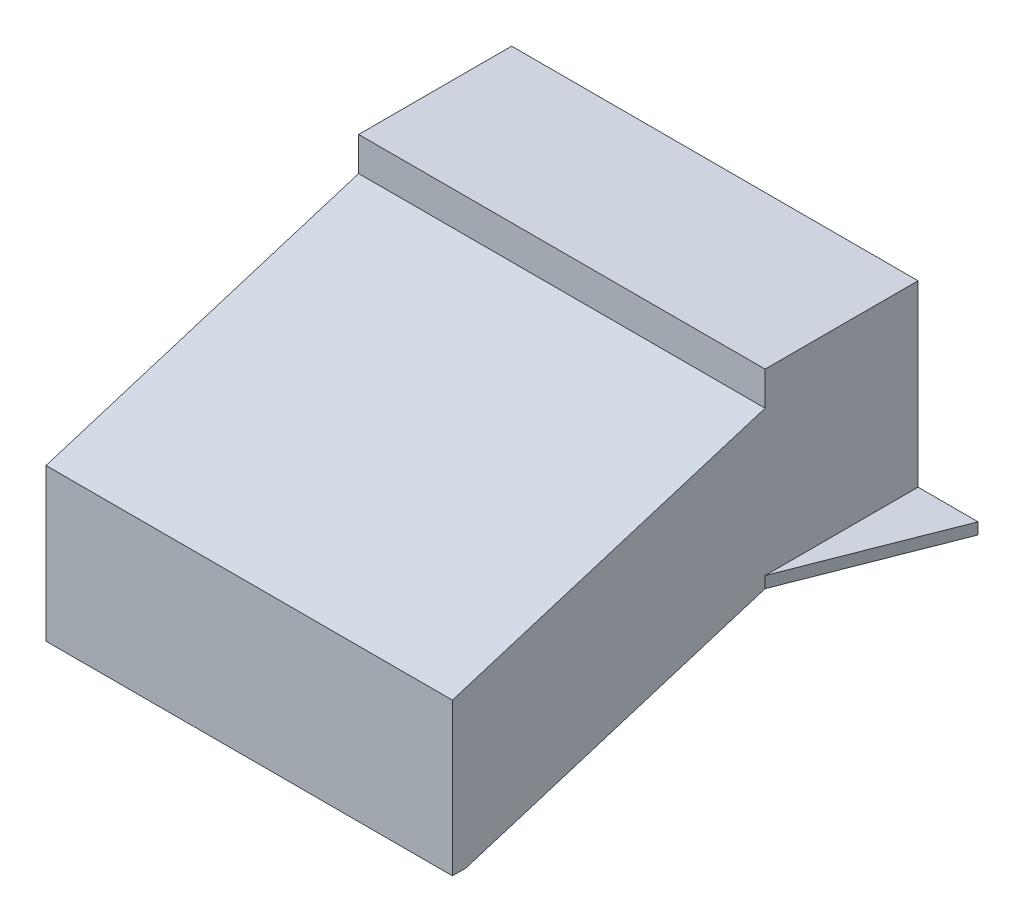
SolidWorks part; units mm, degrees
ref_plane "Front Plane" through (0, 0, 0) normal (0, 0, 1) x (1, 0, 0)
ref_plane "Top Plane" through (0, 0, 0) normal (0, 1, 0) x (1, 0, 0)
ref_plane "Right Plane" through (0, 0, 0) normal (1, 0, 0) x (0, 0, -1)
sketch "Sketch2" plane through (0, 0, 0) normal (0, 1, 0) x (1, 0, 0)
  line L1 (0, 0) -> (91, 0)
  line L2 (0, 0) -> (0, 67)
  line L3 (0, 67) -> (91, 67)
  line L4 (91, 0) -> (91, 67)
  dimension "D1" = 91
  dimension "D2" = 67
extrude "Boss-Extrude10" add sketch "Sketch2" along normal blind 55.68
sketch "Sketch24" plane through (0, 0, 0) normal (-1, 0, 0) x (0, 0, 1)
  line L0 (-67, 0) -> (-67, 20.68)
  line L1 (-67, 55.68) -> (-67, 0) construction
  line L2 (-67, 20.68) -> (0, 0)
  line L3 (0, 0) -> (-67, 0)
extrude "Cut-Extrude13" cut sketch "Sketch24" against normal blind 99
sketch "Sketch26" plane through (0, 0, 0) normal (-1, 0, 0) x (0, 0, 1)
  line L0 (0, 55.68) -> (0, 35)
  line L1 (0, 55.68) -> (0, 0) construction
  line L2 (-67, 55.68) -> (0, 55.68)
  line L3 (0, 35) -> (-67, 55.68)
extrude "Cut-Extrude14" cut sketch "Sketch26" against normal blind 99
sketch "Sketch28" plane through (0, 0, 0) normal (0, -0.9555, -0.2949) x (-1, 0, 0)
  line L0 (0, 0) -> (-2, 0) construction
  line L1 (0, 0) -> (-91, 0) construction
  line L2 (-91, 0) -> (-89, 0) construction
  line L4 (-89, 0) -> (-2, 0)
  line L5 (-89, 0) -> (-89, 97.6529)
  line L6 (-89, 97.6529) -> (-2, 97.6529)
  line L7 (-2, 0) -> (-2, 97.6529)
extrude "Cut-Extrude16" cut sketch "Sketch28" against normal blind 31
sketch "Sketch29" plane through (0, 0, -67) normal (0, 0, -1) x (-1, 0, 0)
  line L1 (-91, 55.68) -> (0, 55.68)
  line L2 (-91, 55.68) -> (-91, 20.68)
  line L3 (-91, 20.68) -> (0, 20.68)
  line L4 (0, 55.68) -> (0, 20.68)
extrude "Boss-Extrude12" add sketch "Sketch29" along normal blind 34.25
sketch "Sketch30" plane through (0, 20.68, 0) normal (0, -1, 0) x (1, 0, 0)
  line L2 (91, -101.25) -> (0, -101.25) construction
  line L3 (89, -67) -> (2, -67)
  line L4 (89, -67) -> (89, -101.25)
  line L5 (89, -101.25) -> (2, -101.25)
  line L6 (2, -67) -> (2, -101.25)
  dimension "D1" = 87
extrude "Cut-Extrude18" cut sketch "Sketch30" against normal blind 32.44
sketch "Sketch31" plane through (0, 0, 0) normal (-1, 0, 0) x (0, 0, 1)
  line L0 (-101.25, 20.68) -> (-101.25, 55.68) construction
  line L1 (-67, 20.68) -> (-101.25, 20.68)
  line L2 (-67, 20.68) -> (-67, 23.2301)
  line L3 (-67, 23.2301) -> (-101.25, 23.2301)
  line L4 (-101.25, 20.68) -> (-101.25, 23.2301)
extrude "Boss-Extrude13" add sketch "Sketch31" along normal blind 13.42
sketch "Sketch32" plane through (91, 0, 0) normal (1, 0, 0) x (0, 0, -1)
  line L0 (101.25, 55.68) -> (101.25, 20.68) construction
  line L1 (67, 20.68) -> (101.25, 20.68)
  line L2 (67, 20.68) -> (67, 23.2389)
  line L3 (67, 23.2389) -> (101.25, 23.2389)
  line L4 (101.25, 20.68) -> (101.25, 23.2389)
extrude "Boss-Extrude14" add sketch "Sketch32" along normal blind 13.42
sketch "Sketch33" plane through (0, 23.2301, 0) normal (0, 1, 0) x (1, 0, 0)
  line L0 (-13.42, 101.25) -> (0, 67)
  line L1 (0, 67) -> (-13.42, 67)
  line L2 (-13.42, 67) -> (-13.42, 101.25)
extrude "Cut-Extrude19" cut sketch "Sketch33" against normal blind 13.42
sketch "Sketch34" plane through (0, 23.2389, 0) normal (0, 1, 0) x (1, 0, 0)
  line L0 (91, 67) -> (104.42, 101.25)
  line L1 (104.42, 101.25) -> (104.42, 67)
  line L2 (104.42, 67) -> (91, 67)
extrude "Cut-Extrude20" cut sketch "Sketch34" against normal blind 13.42
sketch "Sketch35" plane through (0, 0, 0) normal (0, 0, 1) x (1, 0, 0)
  line L1 (0, 35) -> (91, 35)
  line L2 (0, 35) -> (0, 0)
  line L3 (0, 0) -> (91, 0)
  line L4 (91, 35) -> (91, 0)
extrude "Boss-Extrude15" add sketch "Sketch35" along normal blind 3
sketch "Sketch36" plane through (0, 0, 0) normal (-1, 0, 0) x (0, 0, 1)
  line L0 (-16.6501, 40.1392) -> (47759.3308, -14706.2382) construction
  line L2 (0, 35) -> (3, 34.074)
  line L3 (3, 35) -> (3, 0) construction
  line L4 (3, 34.074) -> (3, 35)
  line L5 (3, 35) -> (0, 35)
extrude "Cut-Extrude21" cut sketch "Sketch36" against normal blind 99
ref_plane "Plane1" through (-13.42, 20.68, -101.25) normal (0, -1, 0) x (-1, 0, 0)
sketch "Sketch38" plane through (0, 55.68, 0) normal (0, 1, 0) x (1, 0, 0)
  line L1 (91, 101.25) -> (0, 101.25)
  line L2 (91, 101.25) -> (91, 67)
  line L3 (91, 67) -> (0, 67)
  line L4 (0, 101.25) -> (0, 67)
extrude "Boss-Extrude16" add sketch "Sketch38" along normal blind 7.58
sketch "Sketch40" plane through (0, 53.12, 0) normal (0, -1, 0) x (1, 0, 0)
  line L0 (2, -67) -> (2, -101.25) construction
  line L1 (89, -101.25) -> (2, -101.25)
  line L2 (89, -101.25) -> (89, -69.3197)
  line L3 (89, -69.3197) -> (2, -69.3197)
  line L4 (2, -101.25) -> (2, -69.3197)
extrude "Cut-Extrude23" cut sketch "Sketch40" against normal blind 7.13
